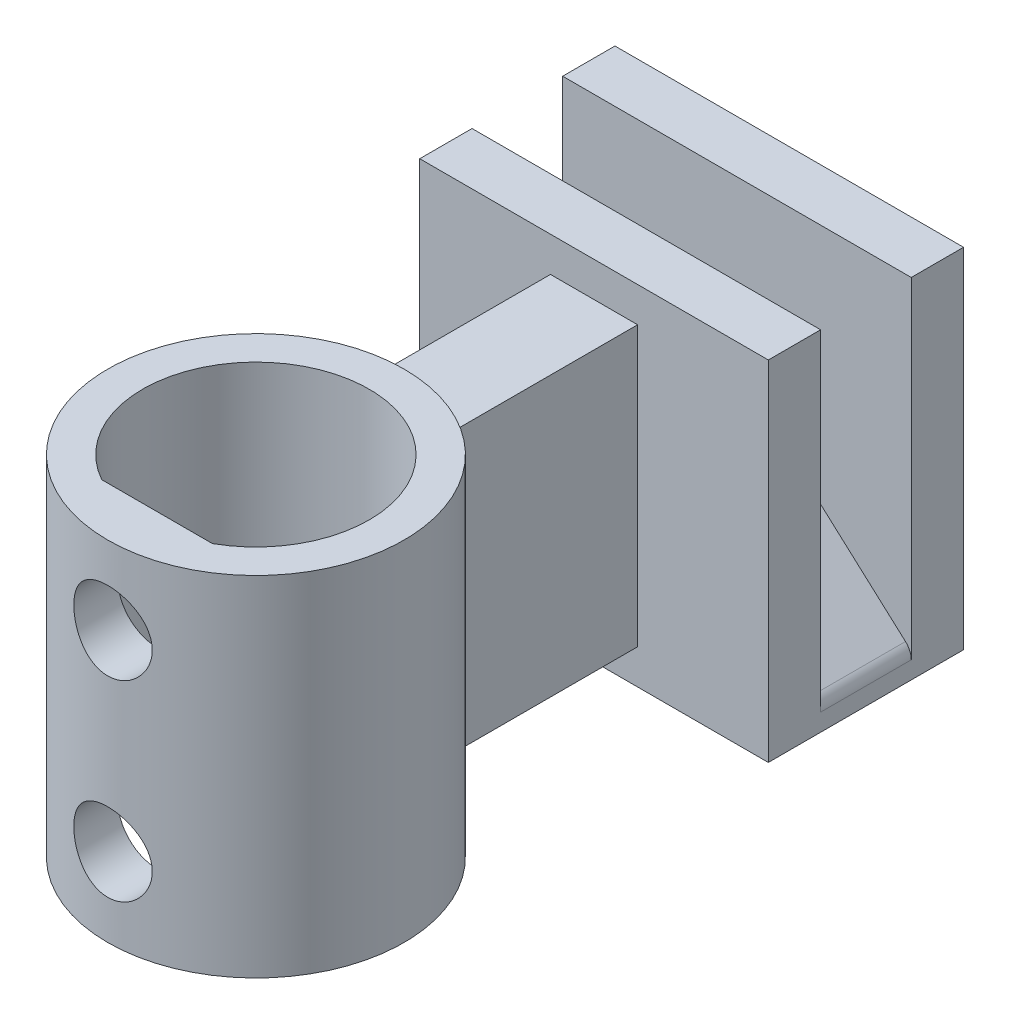
SolidWorks part; units mm, degrees
material "ABS"
ref_plane "Front Plane" through (0, 0, 0) normal (0, 0, 1) x (1, 0, 0)
ref_plane "Top Plane" through (0, 0, 0) normal (0, 1, 0) x (1, 0, 0)
ref_plane "Right Plane" through (0, 0, 0) normal (1, 0, 0) x (0, 0, -1)
sketch "Sketch2" plane through (0, 0, 0) normal (0, 0, 1) x (1, 0, 0)
  line L1 (-10, -5) -> (10, -5)
  line L2 (-10, -5) -> (-10, 5)
  line L3 (-10, 5) -> (10, 5)
  line L4 (10, -5) -> (10, 5)
  line L5 (-10, -5) -> (10, 5) construction
  line L6 (-10, 5) -> (10, -5) construction
  point P0 (0, 0)
  dimension "D1" = 10
  dimension "D2" = 20
extrude "Boss-Extrude1" add sketch "Sketch2" along normal mid plane 5.2
chamfer "Chamfer1" distance 9.5 angle 42 2 edges at (10, 5, 0) (-10, 5, 0)
fillet "Fillet3" radius 1 4 edges at (-10, -3.5538, 0) (10, -3.5538, 0) (0.5, 5, 0) (-0.5, 5, 0)
sketch "Sketch3" plane through (0, 0, 2.6) normal (0, 0, 1) x (1, 0, 0)
  line L0 (-10, -5) -> (10, -5) construction
  line L1 (-10, 15) -> (10, 15)
  line L2 (-10, 15) -> (-10, -5)
  line L3 (-10, -5) -> (10, -5)
  line L4 (10, 15) -> (10, -5)
  line L5 (-10, 15) -> (10, -5) construction
  line L6 (-10, -5) -> (10, 15) construction
  point P0 (0, 5)
  dimension "D1" = 20
  dimension "D2" = 20
extrude "Boss-Extrude2" add sketch "Sketch3" along normal blind 3
mirror "Mirror1" about plane through (0, 0, 0) normal (0, 0, 1) of "Boss-Extrude2"
sketch "Sketch6" plane through (0, 0, 0) normal (0, 1, 0) x (1, 0, 0)
  line L0 (3.175, -30.6718) -> (-3.175, -30.6718)
  arc A0 (3.175, -30.6718) -> (-3.175, -30.6718) centre (0, -25) ccw
  circle A1 centre (0, -25) radius 8.5
  dimension "D1" = 13
  dimension "D2" = 2
  dimension "D3" = 25
  dimension "D4" = 6.35
extrude "Boss-Extrude3" add sketch "Sketch6" along normal up to surface and the other way up to surface separate body up to face at (0, 15, 4.1) other way up to face at (0, -5, 0)
sketch "Sketch5" plane through (0, 0, 5.6) normal (0, 0, 1) x (1, 0, 0)
  line L0 (-10, -5) -> (10, -5) construction
  line L1 (-2.5, 13) -> (2.5, 13)
  line L2 (-2.5, 13) -> (-2.5, -3)
  line L3 (-2.5, -3) -> (2.5, -3)
  line L4 (2.5, 13) -> (2.5, -3)
  line L5 (-2.5, 13) -> (2.5, -3) construction
  line L6 (-2.5, -3) -> (2.5, 13) construction
  line L7 (10, 15) -> (-10, 15) construction
  point P0 (0, 5)
  dimension "D1" = 2
  dimension "D2" = 2
  dimension "D3" = 5
extrude "Boss-Extrude4" add sketch "Sketch5" along normal up to surface (11.276 mm away)
ref_plane "Plane1" through (0, 0, 20) normal (0, 0, 1) x (1, 0, 0)
sketch "Sketch7" plane through (0, 0, 20) normal (0, 0, 1) x (1, 0, 0)
  line L0 (-8.5, -5) -> (8.5, -5) construction
  line L1 (6.5, 15) -> (-6.5, 15) construction
  circle A0 centre (0, 10.5) radius 2.25
  circle A1 centre (0, -0.5) radius 2.25
  dimension "D1" = 4.5
  dimension "D2" = 4.5
  dimension "D3" = 4.5
  dimension "D4" = 4.5
extrude "Cut-Extrude1" cut sketch "Sketch7" along normal up to surface (13.1968 mm away)
